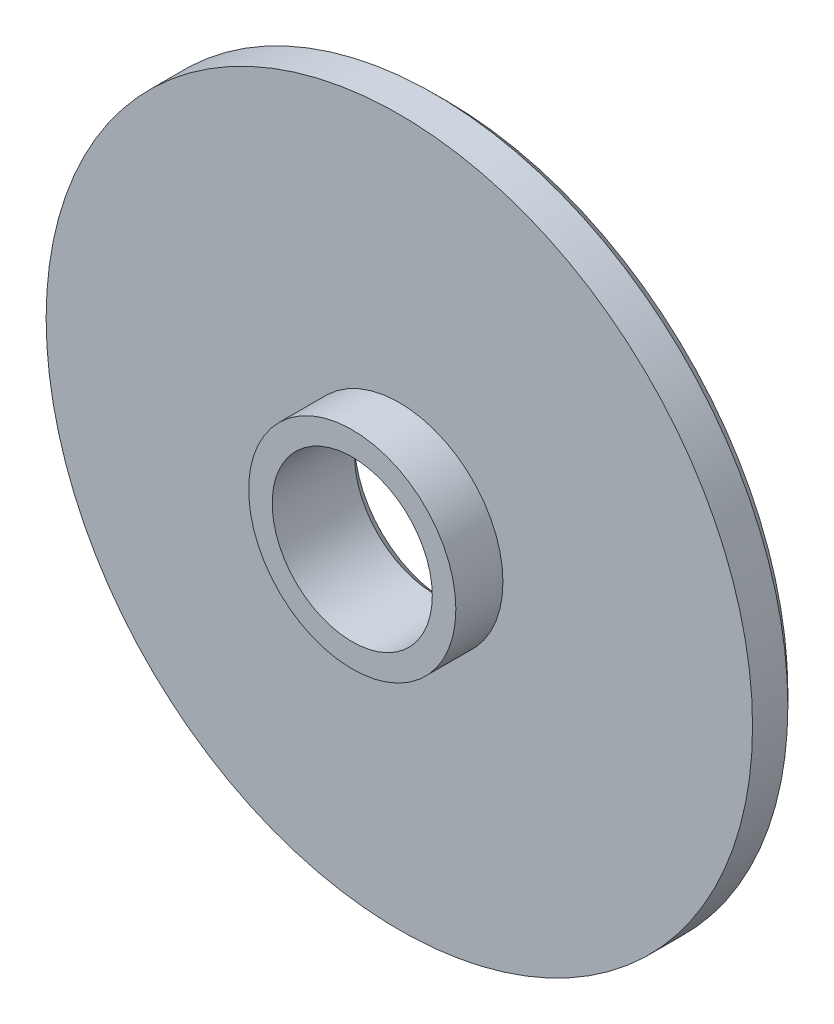
SolidWorks part; units mm, degrees
ref_plane "Front Plane" through (0, 0, 0) normal (0, 0, 1) x (1, 0, 0)
ref_plane "Top Plane" through (0, 0, 0) normal (0, 1, 0) x (1, 0, 0)
ref_plane "Right Plane" through (0, 0, 0) normal (1, 0, 0) x (0, 0, -1)
sketch "Sketch1" plane through (0, 0, 0) normal (0, 0, 1) x (1, 0, 0)
  circle A0 centre (0, 0) radius 1.7
  circle A2 centre (0, 0) radius 7.5
  dimension "D1" = 3.4
  dimension "D2" = 5.8
extrude "Boss-Extrude1" add sketch "Sketch1" along normal blind 1
sketch "Sketch2" plane through (0, 0, 1) normal (0, 0, 1) x (1, 0, 0)
  circle A0 centre (0, 0) radius 1.7
  circle A2 centre (0, 0) radius 2.2
  dimension "D1" = 3.4
  dimension "D2" = 0.5
extrude "Boss-Extrude2" add sketch "Sketch2" along normal blind 1
chamfer "Chamfer1" distance 0.25 angle 45 2 edges at (1.7, 0, 0) (7.5, 0, 0)
